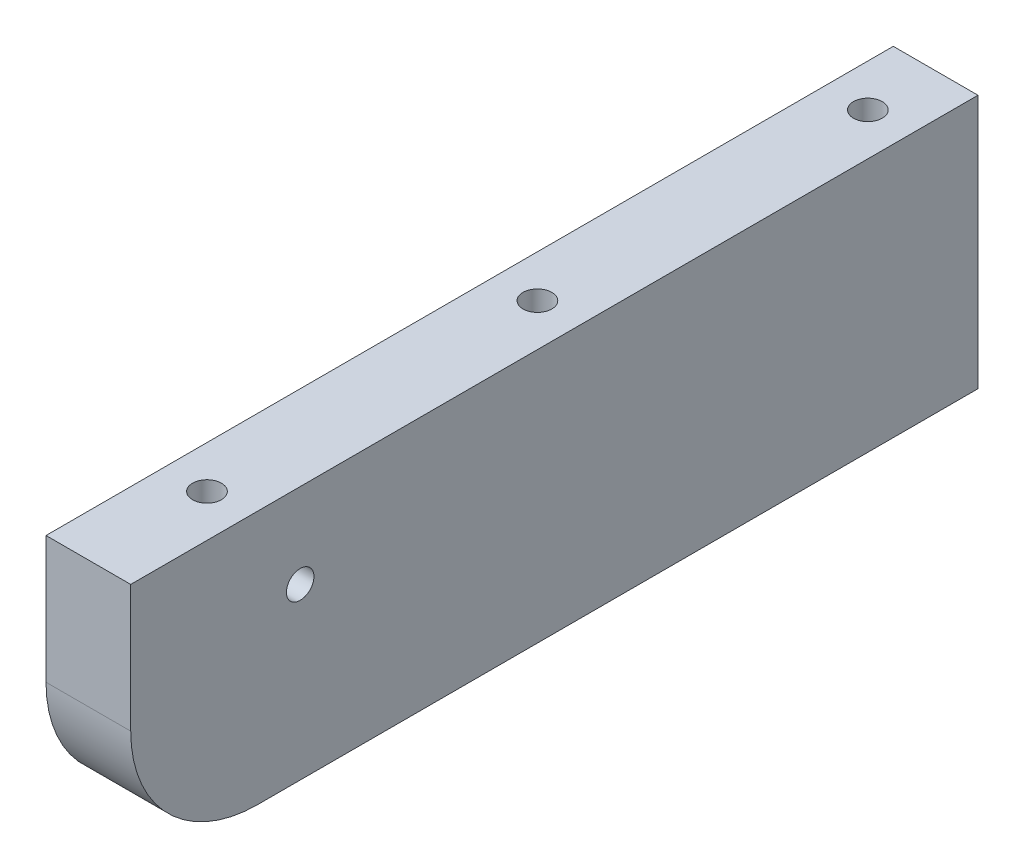
SolidWorks part; units mm, degrees
ref_plane "Front Plane" through (0, 0, 0) normal (0, 0, 1) x (1, 0, 0)
ref_plane "Top Plane" through (0, 0, 0) normal (0, 1, 0) x (1, 0, 0)
ref_plane "Right Plane" through (0, 0, 0) normal (1, 0, 0) x (0, 0, -1)
sketch "Sketch1" plane through (0, 0, 0) normal (1, 0, 0) x (0, 0, -1)
  line L1 (-50, -15) -> (50, -15)
  line L2 (-50, -15) -> (-50, 15)
  line L3 (-50, 15) -> (50, 15)
  line L4 (50, -15) -> (50, 15)
  line L5 (-50, -15) -> (50, 15) construction
  line L6 (-50, 15) -> (50, -15) construction
  circle A0 centre (-30, 5) radius 1.625
  point P0 (0, 0)
  dimension "D3" = 3.25
  dimension "D1" = 30
  dimension "D2" = 100
  dimension "D4" = 20
  dimension "D5" = 10
extrude "Boss-Extrude1" add sketch "Sketch1" along normal blind 10
fillet "Fillet1" radius 15 1 edges at (5, -15, 50)
hole_wizard "CBORE for M3 SHCS" positions "Sketch4" profile "Sketch5" counterbore size "M3" standard "ANSI Metric"
sketch "Sketch4" plane through (-726.2935, 25, -1323.2827) normal (0, 1, 0) x (1, 0, 0)
  line L3 (621.2935, -1281.2827) -> (621.2935, -1365.2827) construction
  line L5 (731.2935, -1281.2827) -> (731.2935, -1359.2827) construction
  circle A0 centre (731.2935, -1281.2827) radius 2.243
  circle A1 centre (731.2935, -1359.2827) radius 2.2384
  circle A3 centre (621.2935, -1281.2827) radius 2.3325
  circle A4 centre (621.2935, -1365.2827) radius 1.7576
  circle A5 centre (621.2935, -1323.2827) radius 1.8624
  circle A6 centre (731.2935, -1320.2827) radius 2.0271
  point P1 (731.2935, -1281.2827)
  point P8 (731.2935, -1359.2827)
  point P15 (621.2935, -1281.2827)
  point P17 (621.2935, -1365.2827)
  point P19 (621.2935, -1323.2827)
  point P27 (731.2935, -1320.2827)
  point P36 (0, 0)
sketch "Sketch5" plane through (5, 25, -42) normal (1, 0, 0) x (0, 0, 1)
  line L0 (0, 0) -> (0, 24.0215)
  line L1 (0, 24.0215) -> (1.7, 23)
  line L2 (1.7, 23) -> (1.7, 3)
  line L3 (1.7, 3) -> (3.25, 3)
  line L4 (3.25, 3) -> (3.25, 0)
  line L5 (3.25, 0) -> (0, 0)
  line L6 (0, 24.0215) -> (-1.7, 23) construction
  line L7 (0, -6.35) -> (0, 107.95) construction
  dimension "Hole Dia." = 3.4
  dimension "Hole Depth" = 23
  dimension "C'Bore Dia." = 6.5
  dimension "C'Bore Depth" = 3
  dimension "Drill Angle" = 118
